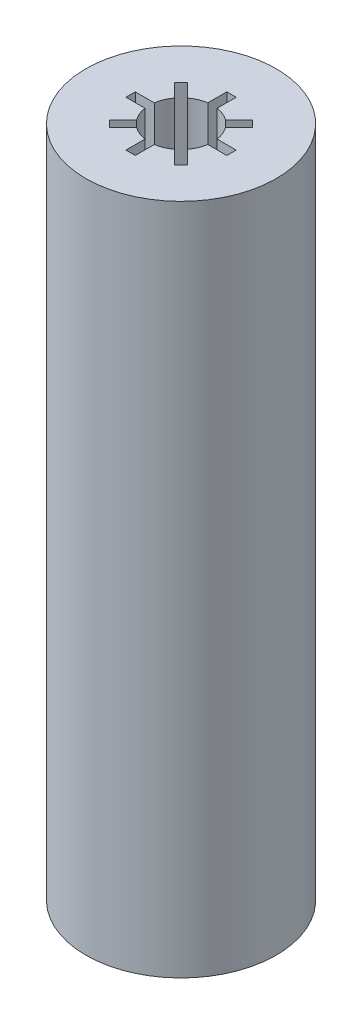
SolidWorks part; units mm, degrees
material "TRT Pourable"
ref_plane "Front Plane" through (0, 0, 0) normal (0, 0, 1) x (1, 0, 0)
ref_plane "Top Plane" through (0, 0, 0) normal (0, 1, 0) x (1, 0, 0)
ref_plane "Right Plane" through (0, 0, 0) normal (1, 0, 0) x (0, 0, -1)
sketch "Sketch1" plane through (0, 0, 0) normal (0, 1, 0) x (1, 0, 0)
  circle A0 centre (0, 0) radius 64.7065
  circle A1 centre (0, 0) radius 21.59
  dimension "D1" = 129.413
  dimension "D2" = 43.18
extrude "Boss-Extrude1" add sketch "Sketch1" along normal blind 457.2
sketch "Sketch2" plane through (0, 457.2, 0) normal (0, 1, 0) x (1, 0, 0)
  line L0 (-3.175, 34.29) -> (3.175, 34.29)
  line L1 (-3.175, 34.29) -> (-3.175, 21.3553)
  line L2 (3.175, 34.29) -> (3.175, 21.3553)
  circle A0 centre (0, 0) radius 21.59 construction
  arc A1 (3.175, 21.3553) -> (-3.175, 21.3553) centre (0, 0) ccw
  point P3 (0, 34.29)
  dimension "D1" = 6.35
  dimension "D2" = 34.29
extrude "Cut-Extrude1" cut sketch "Sketch2" against normal up to next
pattern_circular "CirPattern1" count 8 over 360 about axis through (0, 0, 0) along (0, 1, 0) of "Cut-Extrude1"
